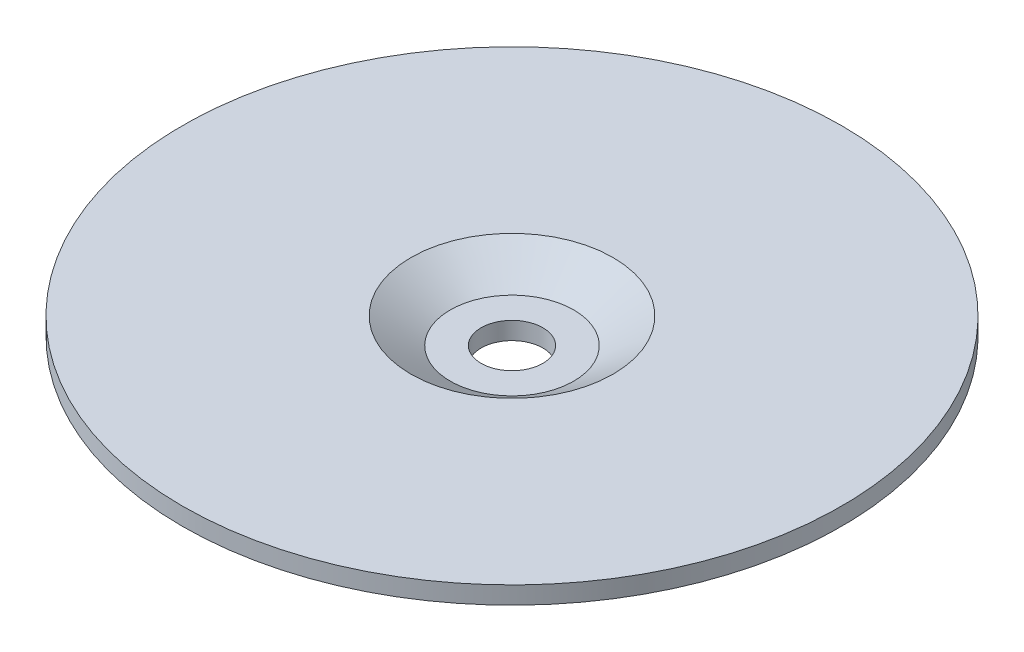
SolidWorks part; units mm, degrees
material "Plain Carbon Steel"
ref_plane "Front Plane" through (0, 0, 0) normal (0, 0, 1) x (1, 0, 0)
ref_plane "Top Plane" through (0, 0, 0) normal (0, 1, 0) x (1, 0, 0)
ref_plane "Right Plane" through (0, 0, 0) normal (1, 0, 0) x (0, 0, -1)
sketch "Sketch1" plane through (0, 0, 0) normal (0, 0, 1) x (1, 0, 0)
  line L0 (0, 0) -> (0, 5.0038) construction
  line L1 (-3.5687, 0) -> (-3.5687, 2.032)
  line L2 (-3.5687, 2.032) -> (-7.1374, 2.032)
  line L3 (-7.1374, 2.032) -> (-11.684, 5.0038)
  line L4 (-11.684, 5.0038) -> (-38.1, 5.0038)
  line L5 (-38.1, 5.0038) -> (-38.1, 2.9718)
  line L6 (-38.1, 2.9718) -> (-11.684, 2.9718)
  line L7 (-11.684, 2.9718) -> (-7.1374, 0)
  line L8 (-7.1374, 0) -> (-3.5687, 0)
  line L9 (-9.4107, 1.4859) -> (-9.4107, 3.5179) construction
  dimension "D1" = 5.0038
  dimension "A" = 7.1374
  dimension "thickness" = 2.032
  dimension "B" = 76.2
  dimension "D" = 23.368
  dimension "C" = 14.2748
revolve "Revolve1" add sketch "Sketch1" angle 360 about L0
